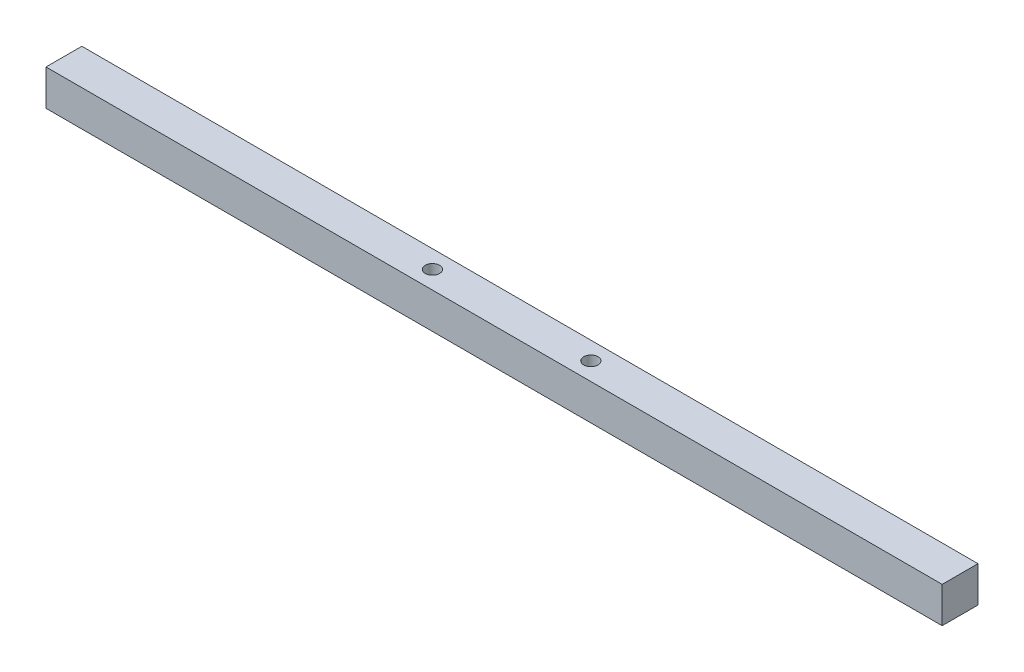
SolidWorks part; units mm, degrees
ref_plane "Front Plane" through (0, 0, 0) normal (0, 0, 1) x (1, 0, 0)
ref_plane "Top Plane" through (0, 0, 0) normal (0, 1, 0) x (1, 0, 0)
ref_plane "Right Plane" through (0, 0, 0) normal (1, 0, 0) x (0, 0, -1)
sketch "Sketch1" plane through (0, 0, 0) normal (1, 0, 0) x (0, 0, -1)
  line L1 (-10, 10) -> (10, 10)
  line L2 (-10, 10) -> (-10, -10)
  line L3 (-10, -10) -> (10, -10)
  line L4 (10, 10) -> (10, -10)
  line L5 (-10, 10) -> (10, -10) construction
  line L6 (-10, -10) -> (10, 10) construction
  point P0 (0, 0)
  dimension "D1" = 20
  dimension "D2" = 20
extrude "Boss-Extrude1" add sketch "Sketch1" along normal blind 500
sketch "Sketch2" plane through (0, 10, 0) normal (0, 1, 0) x (1, 0, 0)
  line L0 (0, 10) -> (0, -10) construction
  circle A0 centre (205.61, 0) radius 4
  circle A1 centre (294, 0) radius 4
  point P6 (0, 0)
  dimension "D1" = 8
  dimension "D2" = 8
  dimension "D3" = 88.39
  dimension "D4" = 205.61
extrude "Cut-Extrude1" cut sketch "Sketch2" against normal through all
